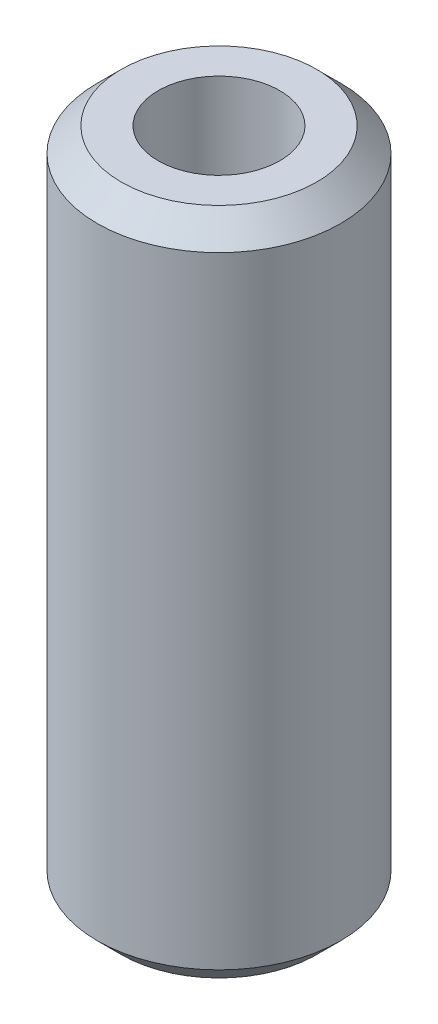
SolidWorks part; units mm, degrees
ref_plane "Front Plane" through (0, 0, 0) normal (0, 0, 1) x (1, 0, 0)
ref_plane "Top Plane" through (0, 0, 0) normal (0, 1, 0) x (1, 0, 0)
ref_plane "Right Plane" through (0, 0, 0) normal (1, 0, 0) x (0, 0, -1)
sketch "Sketch1" plane through (0, 0, 0) normal (0, 1, 0) x (1, 0, 0)
  circle A0 centre (0, 0) radius 12.7
  circle A1 centre (0, 0) radius 6.35
  dimension "D1" = 25.4
  dimension "D2" = 12.7
extrude "Boss-Extrude1" add sketch "Sketch1" along normal mid plane 69.85
chamfer "Chamfer1" distance 2.5 angle 45 2 edges at (0, -34.925, 12.7) (0, 34.925, 12.7)
